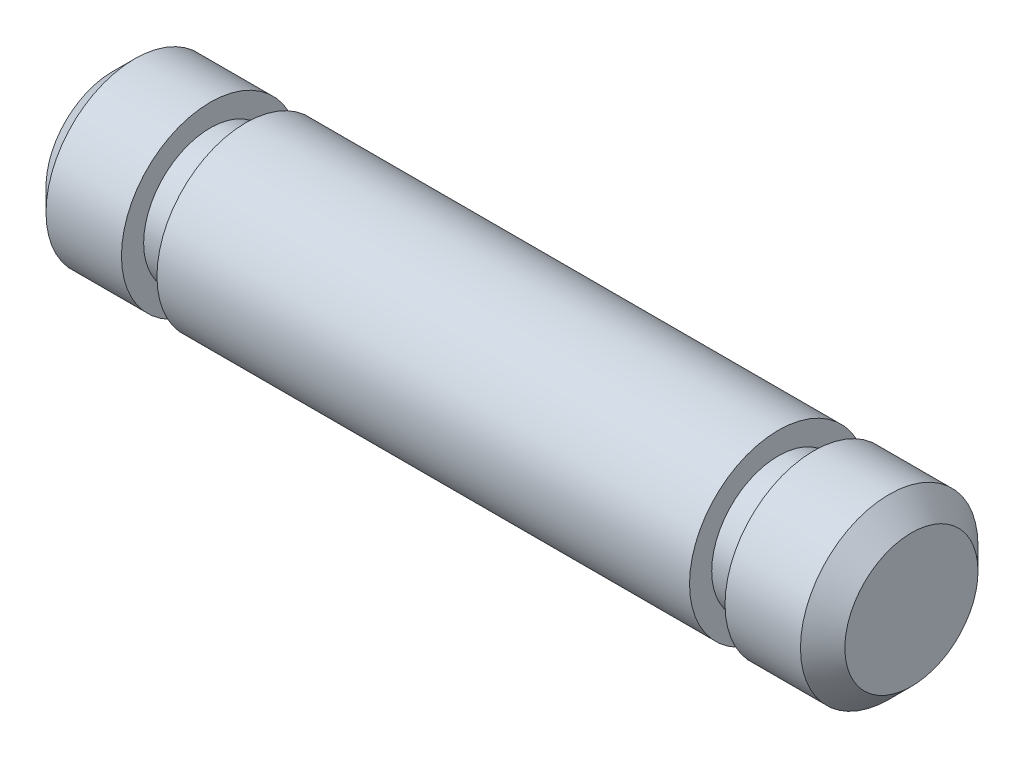
SolidWorks part; units mm, degrees
ref_plane "Front Plane" through (0, 0, 0) normal (0, 0, 1) x (1, 0, 0)
ref_plane "Top Plane" through (0, 0, 0) normal (0, 1, 0) x (1, 0, 0)
ref_plane "Right Plane" through (0, 0, 0) normal (1, 0, 0) x (0, 0, -1)
sketch "Sketch1" plane through (0, 0, 0) normal (1, 0, 0) x (0, 0, -1)
  circle A0 centre (0, 0) radius 2
  dimension "D1" = 4
extrude "Boss-Extrude1" add sketch "Sketch1" along normal mid plane 18
chamfer "Chamfer1" distance 0.5 angle 45 2 edges at (-9, 0, -2) (9, 0, -2)
sketch "Sketch2" plane through (-9, 0, 0) normal (-1, 0, 0) x (0, 0, 1)
  circle A0 centre (0, 0) radius 2 construction
  circle A1 centre (0, 0) radius 2
  circle A2 centre (0, 0) radius 1.5
  dimension "D1" = 3
extrude "Cut-Extrude1" cut sketch "Sketch2" along normal blind 0.8 from offset 3 offset against normal yes
mirror "Mirror2" about plane through (0, 0, 0) normal (1, 0, 0) of "Cut-Extrude1"
